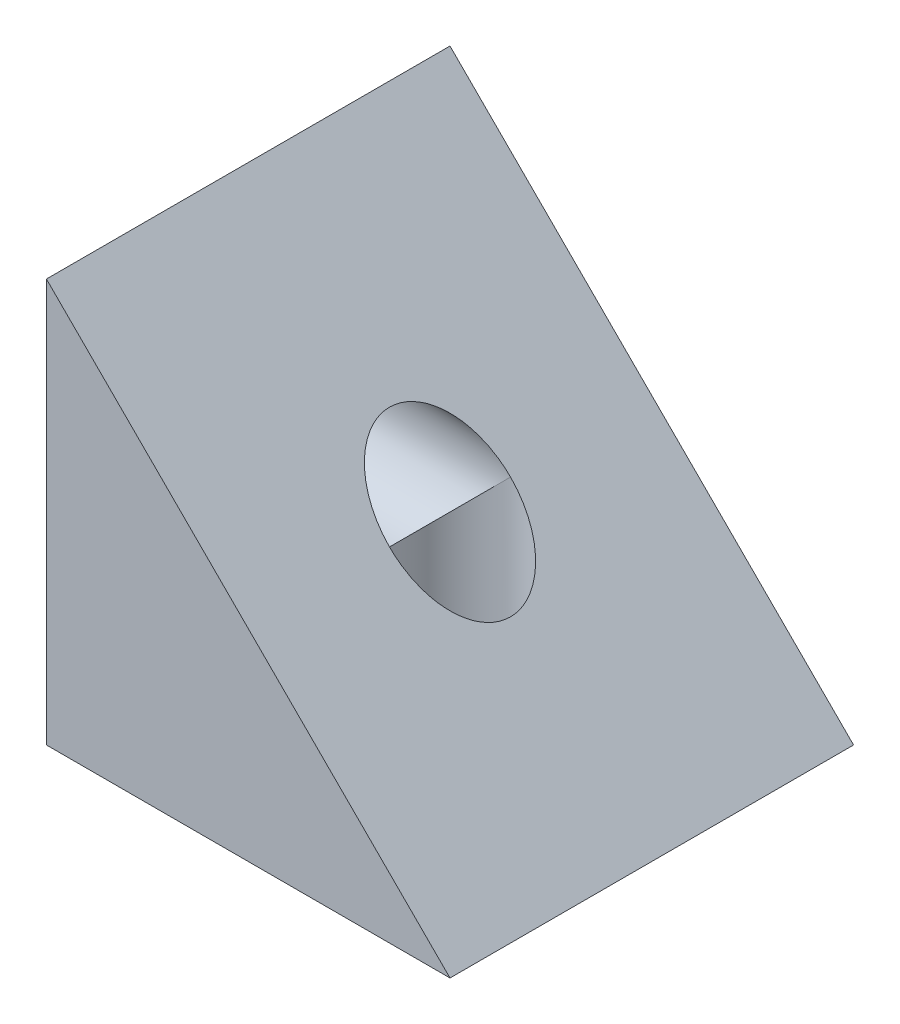
SolidWorks part; units mm, degrees
ref_plane "前视基准面" through (0, 0, 0) normal (0, 0, 1) x (1, 0, 0)
ref_plane "上视基准面" through (0, 0, 0) normal (0, 1, 0) x (1, 0, 0)
ref_plane "右视基准面" through (0, 0, 0) normal (1, 0, 0) x (0, 0, -1)
sketch "草图1" plane through (0, 0, 0) normal (0, 0, 1) x (1, 0, 0)
  line L0 (-5, 5) -> (-5, -5)
  line L1 (-5, -5) -> (5, -5)
  line L2 (5, -5) -> (-5, 5)
  dimension "D1" = 10
extrude "凸台-拉伸1" add sketch "草图1" along normal mid plane 10
sketch "草图2" plane through (-5, 0, 0) normal (-1, 0, 0) x (0, 0, 1)
  circle A0 centre (0, 0) radius 1.5
  dimension "D1" = 3
extrude "切除-拉伸1" cut sketch "草图2" against normal through all both and the other way through all
sketch "草图3" plane through (0, -5, 0) normal (0, -1, 0) x (1, 0, 0)
  circle A0 centre (0, 0) radius 1.5
  dimension "D1" = 3
extrude "切除-拉伸2" cut sketch "草图3" against normal through all both and the other way through all
